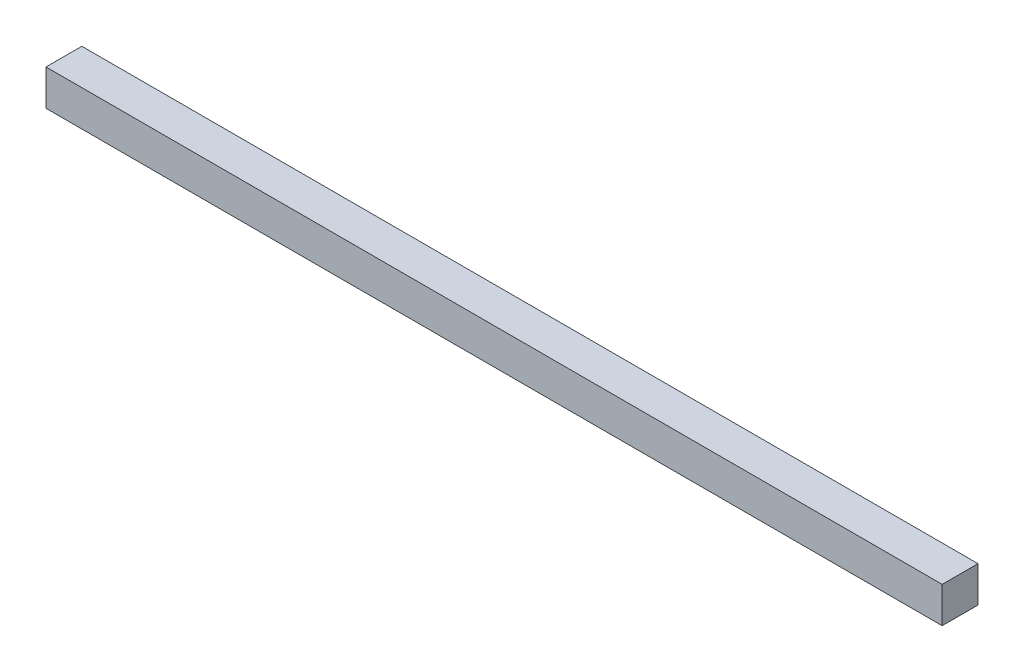
SolidWorks part; units mm, degrees
ref_plane "Front Plane" through (0, 0, 0) normal (0, 0, 1) x (1, 0, 0)
ref_plane "Top Plane" through (0, 0, 0) normal (0, 1, 0) x (1, 0, 0)
ref_plane "Right Plane" through (0, 0, 0) normal (1, 0, 0) x (0, 0, -1)
sketch "Sketch2" plane through (0, 0, 0) normal (0, 0, 1) x (1, 0, 0)
  line L1 (0, 0) -> (100, 0)
  line L2 (0, 0) -> (0, 4)
  line L3 (0, 4) -> (100, 4)
  line L4 (100, 0) -> (100, 4)
  dimension "D1" = 100
  dimension "D2" = 4
extrude "Boss-Extrude1" add sketch "Sketch2" along normal blind 4
